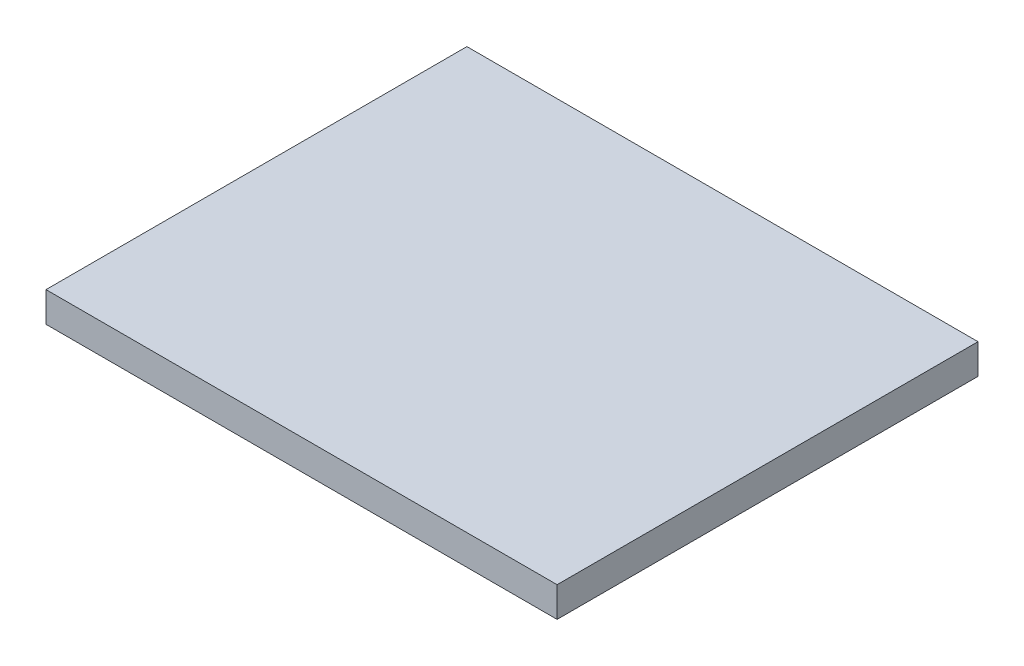
SolidWorks part; units mm, degrees
material "Copper"
ref_plane "Front Plane" through (0, 0, 0) normal (0, 0, 1) x (1, 0, 0)
ref_plane "Top Plane" through (0, 0, 0) normal (0, 1, 0) x (1, 0, 0)
ref_plane "Right Plane" through (0, 0, 0) normal (1, 0, 0) x (0, 0, -1)
sketch "Sketch1" plane through (0, 0, 0) normal (0, 1, 0) x (1, 0, 0)
  line L1 (-85, 70) -> (85, 70)
  line L2 (-85, 70) -> (-85, -70)
  line L3 (-85, -70) -> (85, -70)
  line L4 (85, 70) -> (85, -70)
  line L5 (-85, 70) -> (85, -70) construction
  line L6 (-85, -70) -> (85, 70) construction
  point P0 (0, 0)
  dimension "D1" = 170
  dimension "D2" = 140
extrude "Boss-Extrude1" add sketch "Sketch1" along normal blind 10 contours L2 L3 L4 L1
